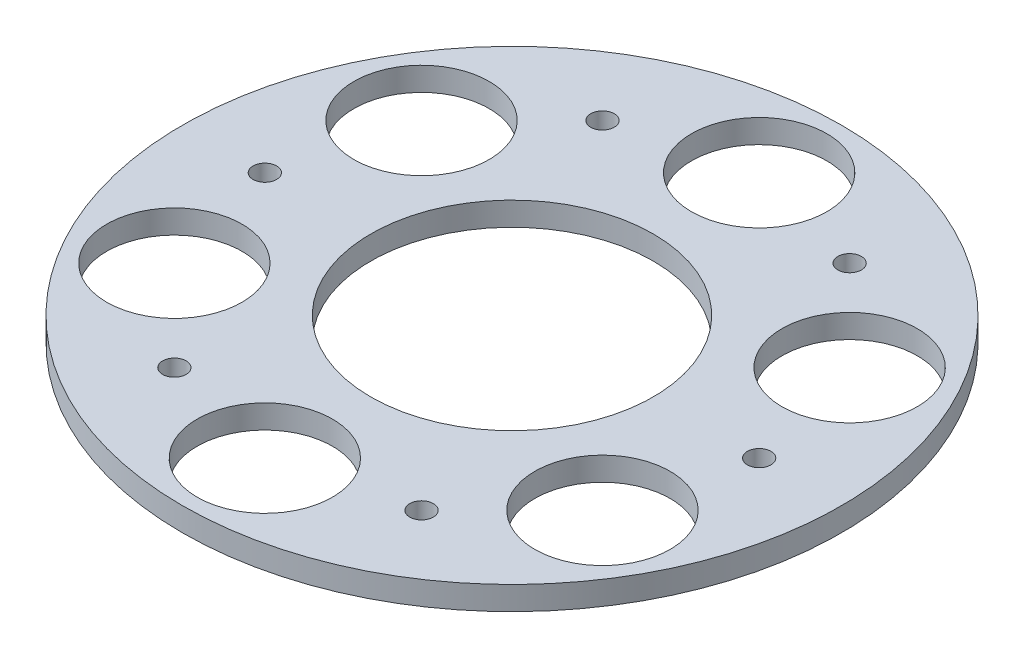
SolidWorks part; units mm, degrees
ref_plane "Płaszczyzna przednia" through (0, 0, 0) normal (0, 0, 1) x (1, 0, 0)
ref_plane "Płaszczyzna górna" through (0, 0, 0) normal (0, 1, 0) x (1, 0, 0)
ref_plane "Płaszczyzna prawa" through (0, 0, 0) normal (1, 0, 0) x (0, 0, -1)
sketch "Sketch1" plane through (0, 0, 0) normal (0, 1, 0) x (1, 0, 0)
  line L0 (0, 0) -> (0, 21) construction
  line L1 (0, 0) -> (10.5, 18.1865) construction
  circle A0 centre (0, 0) radius 28
  circle A1 centre (0, 0) radius 21 construction
  circle A2 centre (0, 21) radius 5.75
  circle A3 centre (18.1865, 10.5) radius 5.75
  circle A4 centre (18.1865, -10.5) radius 5.75
  circle A5 centre (0, -21) radius 5.75
  circle A6 centre (-18.1865, -10.5) radius 5.75
  circle A7 centre (-18.1865, 10.5) radius 5.75
  circle A8 centre (10.5, 18.1865) radius 1
  circle A9 centre (21, 0) radius 1
  circle A10 centre (10.5, -18.1865) radius 1
  circle A11 centre (-10.5, -18.1865) radius 1
  circle A12 centre (-21, 0) radius 1
  circle A13 centre (-10.5, 18.1865) radius 1
  circle A14 centre (0, 0) radius 12
  point P18 (0, 0)
  point P31 (0, 0)
  dimension "D1" = 56
  dimension "D2" = 42
  dimension "D3" = 11.5
  dimension "D6" = 2
  dimension "D8" = 24
  dimension "D5" = 30
  dimension "D4" = 6
  dimension "D7" = 6
extrude "Boss-Extrude1" add sketch "Sketch1" along normal blind 2
